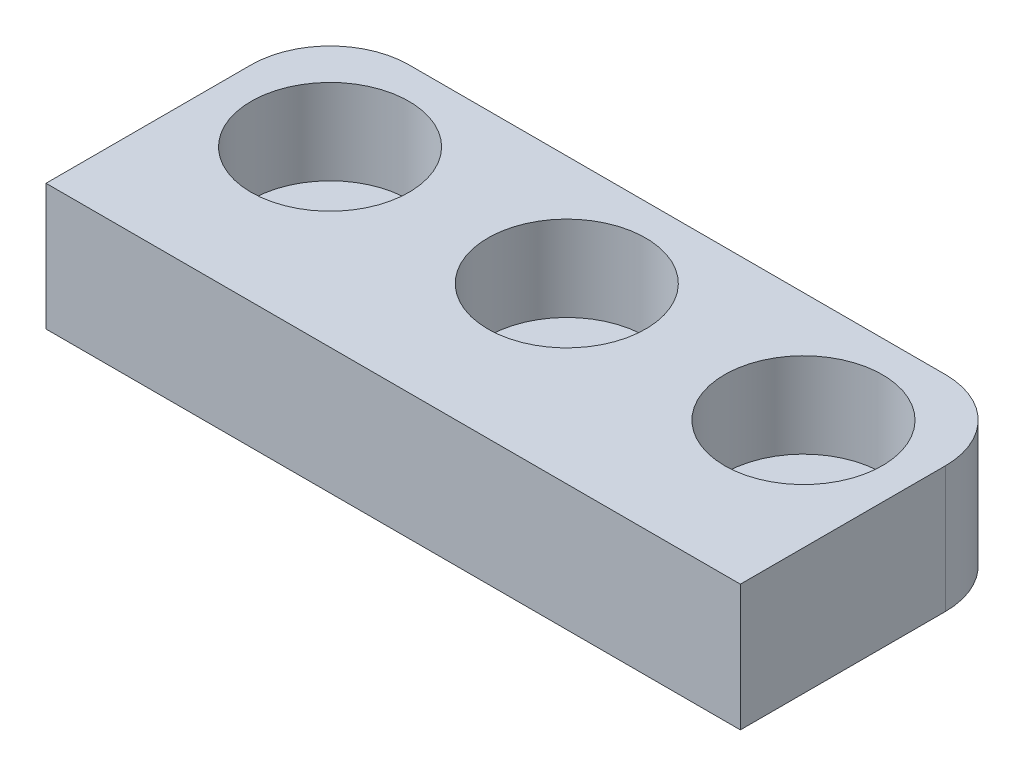
SolidWorks part; units mm, degrees
material "K110"
ref_plane "Front Plane" through (0, 0, 0) normal (0, 0, 1) x (1, 0, 0)
ref_plane "Top Plane" through (0, 0, 0) normal (0, 1, 0) x (1, 0, 0)
ref_plane "Right Plane" through (0, 0, 0) normal (1, 0, 0) x (0, 0, -1)
sketch "Sketch1" plane through (0, 0, 0) normal (0, 1, 0) x (1, 0, 0)
  line L1 (-22, -9) -> (22, -9)
  line L2 (-22, -9) -> (-22, 9)
  line L3 (-22, 9) -> (22, 9)
  line L4 (22, -9) -> (22, 9)
  line L5 (-22, -9) -> (22, 9) construction
  line L6 (-22, 9) -> (22, -9) construction
  point P0 (0, 0)
  dimension "D1" = 44
  dimension "D2" = 18
extrude "Boss-Extrude1" add sketch "Sketch1" against normal blind 8
hole_wizard "CBORE for M5 Hex Socket Head Cap Screw1" positions "Sketch5" profile "Sketch3" counterbore size "M5" standard "ISO" end condition through all
sketch "Sketch5" plane through (0, 0, 0) normal (0, 1, 0) x (1, 0, 0)
  line L0 (0, 9) -> (0, -9) construction
  line L1 (22, 9) -> (-22, 9) construction
  line L2 (-22, -9) -> (22, -9) construction
  point P0 (-15, 2)
  point P2 (0, 2)
  point P5 (15, 2)
  dimension "D1" = 30
  dimension "D2" = 7
sketch "Sketch3" plane through (-15, 0, -2) normal (1, 0, 0) x (0, 0, 1)
  line L0 (0, 0) -> (0, 8)
  line L1 (0, 8) -> (2.65, 8)
  line L3 (2.65, 8) -> (2.65, 5.4)
  line L4 (2.65, 5.4) -> (5, 5.4)
  line L5 (5, 5.4) -> (5, 0)
  line L7 (5, 0) -> (0, 0)
  line L11 (0, -6.35) -> (0, 107.95) construction
  dimension "Thru Hole Dia." = 5.3
  dimension "Thru Hole Depth" = 8
  dimension "C'Bore Dia." = 10
  dimension "C'Bore Depth" = 5.4
fillet "Fillet1" radius 5 2 edges at (22, -4, -9) (-22, -4, -9)
